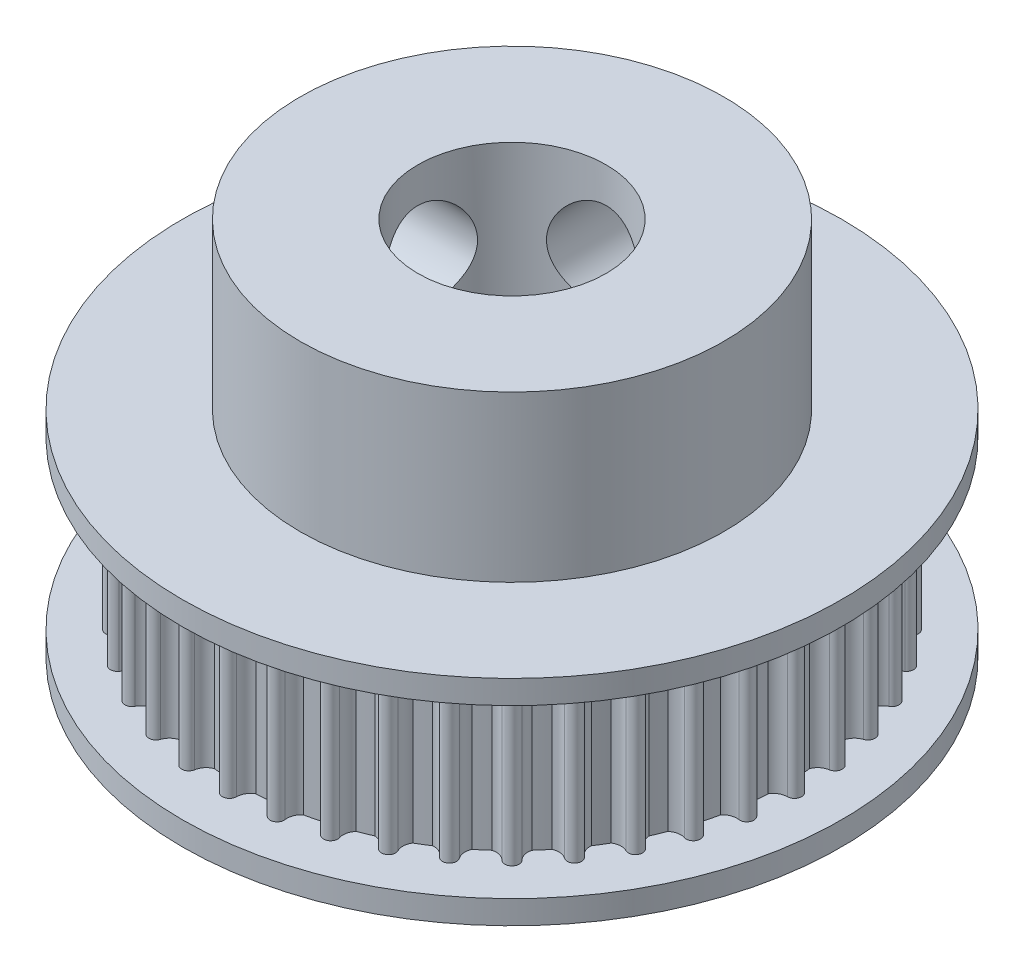
SolidWorks part; units mm, degrees
ref_plane "Front Plane" through (0, 0, 0) normal (0, 0, 1) x (1, 0, 0)
ref_plane "Top Plane" through (0, 0, 0) normal (0, 1, 0) x (1, 0, 0)
ref_plane "Right Plane" through (0, 0, 0) normal (1, 0, 0) x (0, 0, -1)
sketch "Sketch2" plane through (0, 0, 0) normal (0, 1, 0) x (1, 0, 0)
  circle A0 centre (0, 0) radius 14
  circle A1 centre (0, 0) radius 4
  dimension "D1" = 28
  dimension "D2" = 8
extrude "Boss-Extrude1" add sketch "Sketch2" along normal blind 15.5
sketch "Sketch3" plane through (0, 15.5, 0) normal (0, 1, 0) x (1, 0, 0)
  line L0 (0, 0) -> (0, 16.3628) construction
  circle A0 centre (0, 0) radius 14 construction
  circle A1 centre (0, 0) radius 14
  circle A2 centre (0, 0) radius 11.5 construction
  arc A3 (-0.3, 12.0013) -> (0.3, 12.0013) centre (0, 12) cw
  arc A4 (0.3, 12.0013) -> (0.6, 11.4843) centre (0.9, 12.004) ccw
  arc A5 (-0.3, 12.0013) -> (-0.6, 11.4843) centre (-0.9, 12.004) cw
  arc A6 (1.2039, 11.4368) -> (0.6, 11.4843) centre (0, 0) ccw
  arc A7 (1.5811, 11.9005) -> (2.1737, 11.8066) centre (1.8772, 11.8523) cw
  arc A8 (1.5811, 11.9005) -> (1.2039, 11.4368) centre (0.9889, 11.997) cw
  arc A9 (2.1737, 11.8066) -> (2.3892, 11.2491) centre (2.7667, 11.7154) ccw
  arc A10 (2.9782, 11.1077) -> (2.3892, 11.2491) centre (0, 0) ccw
  arc A11 (3.4233, 11.5066) -> (3.9939, 11.3212) centre (3.7082, 11.4127) cw
  arc A12 (3.4233, 11.5066) -> (2.9782, 11.1077) centre (2.8535, 11.6946) cw
  arc A13 (3.9939, 11.3212) -> (4.1195, 10.7368) centre (4.5654, 11.1383) ccw
  arc A14 (4.6792, 10.505) -> (4.1195, 10.7368) centre (0, 0) ccw
  arc A15 (5.1812, 10.8295) -> (5.7158, 10.5571) centre (5.4479, 10.6921) cw
  arc A16 (5.1812, 10.8295) -> (4.6792, 10.505) centre (4.6478, 11.1042) cw
  arc A17 (5.7158, 10.5571) -> (5.7484, 9.9602) centre (6.2516, 10.287) ccw
  arc A18 (6.2649, 9.6437) -> (5.7484, 9.9602) centre (0, 0) ccw
  arc A19 (6.8115, 9.8856) -> (7.2969, 9.5329) centre (7.0534, 9.7082) cw
  arc A20 (6.8115, 9.8856) -> (6.2649, 9.6437) centre (6.3276, 10.2404) cw
  arc A21 (7.2969, 9.5329) -> (7.2357, 8.9384) centre (7.7839, 9.1824) ccw
  arc A22 (7.6964, 8.5449) -> (7.2357, 8.9384) centre (0, 0) ccw
  arc A23 (8.2741, 8.6983) -> (8.6983, 8.2741) centre (8.4853, 8.4853) cw
  arc A24 (8.2741, 8.6983) -> (7.6964, 8.5449) centre (7.8517, 9.1245) cw
  arc A25 (8.6983, 8.2741) -> (8.5449, 7.6964) centre (9.1245, 7.8517) ccw
  arc A26 (8.9384, 7.2357) -> (8.5449, 7.6964) centre (0, 0) ccw
  arc A27 (9.5329, 7.2969) -> (9.8856, 6.8115) centre (9.7082, 7.0534) cw
  arc A28 (9.5329, 7.2969) -> (8.9384, 7.2357) centre (9.1824, 7.7839) cw
  arc A29 (9.8856, 6.8115) -> (9.6437, 6.2649) centre (10.2404, 6.3276) ccw
  arc A30 (9.9602, 5.7484) -> (9.6437, 6.2649) centre (0, 0) ccw
  arc A31 (10.5571, 5.7158) -> (10.8295, 5.1812) centre (10.6921, 5.4479) cw
  arc A32 (10.5571, 5.7158) -> (9.9602, 5.7484) centre (10.287, 6.2516) cw
  arc A33 (10.8295, 5.1812) -> (10.505, 4.6792) centre (11.1042, 4.6478) ccw
  arc A34 (10.7368, 4.1195) -> (10.505, 4.6792) centre (0, 0) ccw
  arc A35 (11.3212, 3.9939) -> (11.5066, 3.4233) centre (11.4127, 3.7082) cw
  arc A36 (11.3212, 3.9939) -> (10.7368, 4.1195) centre (11.1383, 4.5654) cw
  arc A37 (11.5066, 3.4233) -> (11.1077, 2.9782) centre (11.6946, 2.8535) ccw
  arc A38 (11.2491, 2.3892) -> (11.1077, 2.9782) centre (0, 0) ccw
  arc A39 (11.8066, 2.1737) -> (11.9005, 1.5811) centre (11.8523, 1.8772) cw
  arc A40 (11.8066, 2.1737) -> (11.2491, 2.3892) centre (11.7154, 2.7667) cw
  arc A41 (11.9005, 1.5811) -> (11.4368, 1.2039) centre (11.997, 0.9889) ccw
  arc A42 (11.4843, 0.6) -> (11.4368, 1.2039) centre (0, 0) ccw
  arc A43 (12.0013, 0.3) -> (12.0013, -0.3) centre (12, 0) cw
  arc A44 (12.0013, 0.3) -> (11.4843, 0.6) centre (12.004, 0.9) cw
  arc A45 (12.0013, -0.3) -> (11.4843, -0.6) centre (12.004, -0.9) ccw
  arc A46 (11.4368, -1.2039) -> (11.4843, -0.6) centre (0, 0) ccw
  arc A47 (11.9005, -1.5811) -> (11.8066, -2.1737) centre (11.8523, -1.8772) cw
  arc A48 (11.9005, -1.5811) -> (11.4368, -1.2039) centre (11.997, -0.9889) cw
  arc A49 (11.8066, -2.1737) -> (11.2491, -2.3892) centre (11.7154, -2.7667) ccw
  arc A50 (11.1077, -2.9782) -> (11.2491, -2.3892) centre (0, 0) ccw
  arc A51 (11.5066, -3.4233) -> (11.3212, -3.9939) centre (11.4127, -3.7082) cw
  arc A52 (11.5066, -3.4233) -> (11.1077, -2.9782) centre (11.6946, -2.8535) cw
  arc A53 (11.3212, -3.9939) -> (10.7368, -4.1195) centre (11.1383, -4.5654) ccw
  arc A54 (10.505, -4.6792) -> (10.7368, -4.1195) centre (0, 0) ccw
  arc A55 (10.8295, -5.1812) -> (10.5571, -5.7158) centre (10.6921, -5.4479) cw
  arc A56 (10.8295, -5.1812) -> (10.505, -4.6792) centre (11.1042, -4.6478) cw
  arc A57 (10.5571, -5.7158) -> (9.9602, -5.7484) centre (10.287, -6.2516) ccw
  arc A58 (9.6437, -6.2649) -> (9.9602, -5.7484) centre (0, 0) ccw
  arc A59 (9.8856, -6.8115) -> (9.5329, -7.2969) centre (9.7082, -7.0534) cw
  arc A60 (9.8856, -6.8115) -> (9.6437, -6.2649) centre (10.2404, -6.3276) cw
  arc A61 (9.5329, -7.2969) -> (8.9384, -7.2357) centre (9.1824, -7.7839) ccw
  arc A62 (8.5449, -7.6964) -> (8.9384, -7.2357) centre (0, 0) ccw
  arc A63 (8.6983, -8.2741) -> (8.2741, -8.6983) centre (8.4853, -8.4853) cw
  arc A64 (8.6983, -8.2741) -> (8.5449, -7.6964) centre (9.1245, -7.8517) cw
  arc A65 (8.2741, -8.6983) -> (7.6964, -8.5449) centre (7.8517, -9.1245) ccw
  arc A66 (7.2357, -8.9384) -> (7.6964, -8.5449) centre (0, 0) ccw
  arc A67 (7.2969, -9.5329) -> (6.8115, -9.8856) centre (7.0534, -9.7082) cw
  arc A68 (7.2969, -9.5329) -> (7.2357, -8.9384) centre (7.7839, -9.1824) cw
  arc A69 (6.8115, -9.8856) -> (6.2649, -9.6437) centre (6.3276, -10.2404) ccw
  arc A70 (5.7484, -9.9602) -> (6.2649, -9.6437) centre (0, 0) ccw
  arc A71 (5.7158, -10.5571) -> (5.1812, -10.8295) centre (5.4479, -10.6921) cw
  arc A72 (5.7158, -10.5571) -> (5.7484, -9.9602) centre (6.2516, -10.287) cw
  arc A73 (5.1812, -10.8295) -> (4.6792, -10.505) centre (4.6478, -11.1042) ccw
  arc A74 (4.1195, -10.7368) -> (4.6792, -10.505) centre (0, 0) ccw
  arc A75 (3.9939, -11.3212) -> (3.4233, -11.5066) centre (3.7082, -11.4127) cw
  arc A76 (3.9939, -11.3212) -> (4.1195, -10.7368) centre (4.5654, -11.1383) cw
  arc A77 (3.4233, -11.5066) -> (2.9782, -11.1077) centre (2.8535, -11.6946) ccw
  arc A78 (2.3892, -11.2491) -> (2.9782, -11.1077) centre (0, 0) ccw
  arc A79 (2.1737, -11.8066) -> (1.5811, -11.9005) centre (1.8772, -11.8523) cw
  arc A80 (2.1737, -11.8066) -> (2.3892, -11.2491) centre (2.7667, -11.7154) cw
  arc A81 (1.5811, -11.9005) -> (1.2039, -11.4368) centre (0.9889, -11.997) ccw
  arc A82 (0.6, -11.4843) -> (1.2039, -11.4368) centre (0, 0) ccw
  arc A83 (0.3, -12.0013) -> (-0.3, -12.0013) centre (0, -12) cw
  arc A84 (0.3, -12.0013) -> (0.6, -11.4843) centre (0.9, -12.004) cw
  arc A85 (-0.3, -12.0013) -> (-0.6, -11.4843) centre (-0.9, -12.004) ccw
  arc A86 (-1.2039, -11.4368) -> (-0.6, -11.4843) centre (0, 0) ccw
  arc A87 (-1.5811, -11.9005) -> (-2.1737, -11.8066) centre (-1.8772, -11.8523) cw
  arc A88 (-1.5811, -11.9005) -> (-1.2039, -11.4368) centre (-0.9889, -11.997) cw
  arc A89 (-2.1737, -11.8066) -> (-2.3892, -11.2491) centre (-2.7667, -11.7154) ccw
  arc A90 (-2.9782, -11.1077) -> (-2.3892, -11.2491) centre (0, 0) ccw
  arc A91 (-3.4233, -11.5066) -> (-3.9939, -11.3212) centre (-3.7082, -11.4127) cw
  arc A92 (-3.4233, -11.5066) -> (-2.9782, -11.1077) centre (-2.8535, -11.6946) cw
  arc A93 (-3.9939, -11.3212) -> (-4.1195, -10.7368) centre (-4.5654, -11.1383) ccw
  arc A94 (-4.6792, -10.505) -> (-4.1195, -10.7368) centre (0, 0) ccw
  arc A95 (-5.1812, -10.8295) -> (-5.7158, -10.5571) centre (-5.4479, -10.6921) cw
  arc A96 (-5.1812, -10.8295) -> (-4.6792, -10.505) centre (-4.6478, -11.1042) cw
  arc A97 (-5.7158, -10.5571) -> (-5.7484, -9.9602) centre (-6.2516, -10.287) ccw
  arc A98 (-6.2649, -9.6437) -> (-5.7484, -9.9602) centre (0, 0) ccw
  arc A99 (-6.8115, -9.8856) -> (-7.2969, -9.5329) centre (-7.0534, -9.7082) cw
  arc A100 (-6.8115, -9.8856) -> (-6.2649, -9.6437) centre (-6.3276, -10.2404) cw
  arc A101 (-7.2969, -9.5329) -> (-7.2357, -8.9384) centre (-7.7839, -9.1824) ccw
  arc A102 (-7.6964, -8.5449) -> (-7.2357, -8.9384) centre (0, 0) ccw
  arc A103 (-8.2741, -8.6983) -> (-8.6983, -8.2741) centre (-8.4853, -8.4853) cw
  arc A104 (-8.2741, -8.6983) -> (-7.6964, -8.5449) centre (-7.8517, -9.1245) cw
  arc A105 (-8.6983, -8.2741) -> (-8.5449, -7.6964) centre (-9.1245, -7.8517) ccw
  arc A106 (-8.9384, -7.2357) -> (-8.5449, -7.6964) centre (0, 0) ccw
  arc A107 (-9.5329, -7.2969) -> (-9.8856, -6.8115) centre (-9.7082, -7.0534) cw
  arc A108 (-9.5329, -7.2969) -> (-8.9384, -7.2357) centre (-9.1824, -7.7839) cw
  arc A109 (-9.8856, -6.8115) -> (-9.6437, -6.2649) centre (-10.2404, -6.3276) ccw
  arc A110 (-9.9602, -5.7484) -> (-9.6437, -6.2649) centre (0, 0) ccw
  arc A111 (-10.5571, -5.7158) -> (-10.8295, -5.1812) centre (-10.6921, -5.4479) cw
  arc A112 (-10.5571, -5.7158) -> (-9.9602, -5.7484) centre (-10.287, -6.2516) cw
  arc A113 (-10.8295, -5.1812) -> (-10.505, -4.6792) centre (-11.1042, -4.6478) ccw
  arc A114 (-10.7368, -4.1195) -> (-10.505, -4.6792) centre (0, 0) ccw
  arc A115 (-11.3212, -3.9939) -> (-11.5066, -3.4233) centre (-11.4127, -3.7082) cw
  arc A116 (-11.3212, -3.9939) -> (-10.7368, -4.1195) centre (-11.1383, -4.5654) cw
  arc A117 (-11.5066, -3.4233) -> (-11.1077, -2.9782) centre (-11.6946, -2.8535) ccw
  arc A118 (-11.2491, -2.3892) -> (-11.1077, -2.9782) centre (0, 0) ccw
  arc A119 (-11.8066, -2.1737) -> (-11.9005, -1.5811) centre (-11.8523, -1.8772) cw
  arc A120 (-11.8066, -2.1737) -> (-11.2491, -2.3892) centre (-11.7154, -2.7667) cw
  arc A121 (-11.9005, -1.5811) -> (-11.4368, -1.2039) centre (-11.997, -0.9889) ccw
  arc A122 (-11.4843, -0.6) -> (-11.4368, -1.2039) centre (0, 0) ccw
  arc A123 (-12.0013, -0.3) -> (-12.0013, 0.3) centre (-12, 0) cw
  arc A124 (-12.0013, -0.3) -> (-11.4843, -0.6) centre (-12.004, -0.9) cw
  arc A125 (-12.0013, 0.3) -> (-11.4843, 0.6) centre (-12.004, 0.9) ccw
  arc A126 (-11.4368, 1.2039) -> (-11.4843, 0.6) centre (0, 0) ccw
  arc A127 (-11.9005, 1.5811) -> (-11.8066, 2.1737) centre (-11.8523, 1.8772) cw
  arc A128 (-11.9005, 1.5811) -> (-11.4368, 1.2039) centre (-11.997, 0.9889) cw
  arc A129 (-11.8066, 2.1737) -> (-11.2491, 2.3892) centre (-11.7154, 2.7667) ccw
  arc A130 (-11.1077, 2.9782) -> (-11.2491, 2.3892) centre (0, 0) ccw
  arc A131 (-11.5066, 3.4233) -> (-11.3212, 3.9939) centre (-11.4127, 3.7082) cw
  arc A132 (-11.5066, 3.4233) -> (-11.1077, 2.9782) centre (-11.6946, 2.8535) cw
  arc A133 (-11.3212, 3.9939) -> (-10.7368, 4.1195) centre (-11.1383, 4.5654) ccw
  arc A134 (-10.505, 4.6792) -> (-10.7368, 4.1195) centre (0, 0) ccw
  arc A135 (-10.8295, 5.1812) -> (-10.5571, 5.7158) centre (-10.6921, 5.4479) cw
  arc A136 (-10.8295, 5.1812) -> (-10.505, 4.6792) centre (-11.1042, 4.6478) cw
  arc A137 (-10.5571, 5.7158) -> (-9.9602, 5.7484) centre (-10.287, 6.2516) ccw
  arc A138 (-9.6437, 6.2649) -> (-9.9602, 5.7484) centre (0, 0) ccw
  arc A139 (-9.8856, 6.8115) -> (-9.5329, 7.2969) centre (-9.7082, 7.0534) cw
  arc A140 (-9.8856, 6.8115) -> (-9.6437, 6.2649) centre (-10.2404, 6.3276) cw
  arc A141 (-9.5329, 7.2969) -> (-8.9384, 7.2357) centre (-9.1824, 7.7839) ccw
  arc A142 (-8.5449, 7.6964) -> (-8.9384, 7.2357) centre (0, 0) ccw
  arc A143 (-8.6983, 8.2741) -> (-8.2741, 8.6983) centre (-8.4853, 8.4853) cw
  arc A144 (-8.6983, 8.2741) -> (-8.5449, 7.6964) centre (-9.1245, 7.8517) cw
  arc A145 (-8.2741, 8.6983) -> (-7.6964, 8.5449) centre (-7.8517, 9.1245) ccw
  arc A146 (-7.2357, 8.9384) -> (-7.6964, 8.5449) centre (0, 0) ccw
  arc A147 (-7.2969, 9.5329) -> (-6.8115, 9.8856) centre (-7.0534, 9.7082) cw
  arc A148 (-7.2969, 9.5329) -> (-7.2357, 8.9384) centre (-7.7839, 9.1824) cw
  arc A149 (-6.8115, 9.8856) -> (-6.2649, 9.6437) centre (-6.3276, 10.2404) ccw
  arc A150 (-5.7484, 9.9602) -> (-6.2649, 9.6437) centre (0, 0) ccw
  arc A151 (-5.7158, 10.5571) -> (-5.1812, 10.8295) centre (-5.4479, 10.6921) cw
  arc A152 (-5.7158, 10.5571) -> (-5.7484, 9.9602) centre (-6.2516, 10.287) cw
  arc A153 (-5.1812, 10.8295) -> (-4.6792, 10.505) centre (-4.6478, 11.1042) ccw
  arc A154 (-4.1195, 10.7368) -> (-4.6792, 10.505) centre (0, 0) ccw
  arc A155 (-3.9939, 11.3212) -> (-3.4233, 11.5066) centre (-3.7082, 11.4127) cw
  arc A156 (-3.9939, 11.3212) -> (-4.1195, 10.7368) centre (-4.5654, 11.1383) cw
  arc A157 (-3.4233, 11.5066) -> (-2.9782, 11.1077) centre (-2.8535, 11.6946) ccw
  arc A158 (-2.3892, 11.2491) -> (-2.9782, 11.1077) centre (0, 0) ccw
  arc A159 (-2.1737, 11.8066) -> (-1.5811, 11.9005) centre (-1.8772, 11.8523) cw
  arc A160 (-2.1737, 11.8066) -> (-2.3892, 11.2491) centre (-2.7667, 11.7154) cw
  arc A161 (-1.5811, 11.9005) -> (-1.2039, 11.4368) centre (-0.9889, 11.997) ccw
  arc A162 (-0.6, 11.4843) -> (-1.2039, 11.4368) centre (0, 0) ccw
  point P31 (1.2289, 11.447)
  point P328 (0, 0)
  dimension "D1" = 23
  dimension "D4" = 0.6
  dimension "D2" = 0.3
  dimension "D3" = 0.3
  dimension "D5" = 12
extrude "Cut-Extrude1" cut sketch "Sketch3" against normal blind 7.1 from offset 1 offset against normal yes
sketch "Sketch4" plane through (0, 0, 0) normal (0, 0, 1) x (1, 0, 0)
  circle A0 centre (0, 3.75) radius 2
  dimension "D1" = 4
  dimension "D2" = 3.75
extrude "Cut-Extrude2" cut sketch "Sketch4" against normal up to next
sketch "Sketch5" plane through (0, 0, 0) normal (1, 0, 0) x (0, 0, -1)
  circle A0 centre (0, 3.75) radius 2
  dimension "D1" = 4
  dimension "D2" = 3.75
extrude "Cut-Extrude3" cut sketch "Sketch5" against normal up to next
sketch "Sketch6" plane through (0, 15.5, 0) normal (0, 1, 0) x (1, 0, 0)
  circle A0 centre (0, 0) radius 9
  circle A1 centre (0, 0) radius 4 construction
  circle A2 centre (0, 0) radius 4
  dimension "D1" = 18
extrude "Boss-Extrude2" add sketch "Sketch6" along normal blind 7
sketch "Sketch7" plane through (0, 0, 0) normal (0, 0, 1) x (1, 0, 0)
  line L0 (9, 22.5) -> (-9, 22.5) construction
  circle A0 centre (0, 19) radius 2
  dimension "D1" = 4
  dimension "D2" = 3.5
extrude "Cut-Extrude4" cut sketch "Sketch7" against normal up to next
sketch "Sketch8" plane through (0, 0, 0) normal (1, 0, 0) x (0, 0, -1)
  line L0 (9, 22.5) -> (-9, 22.5) construction
  circle A0 centre (0, 19) radius 2
  dimension "D1" = 4
  dimension "D2" = 3.5
extrude "Cut-Extrude5" cut sketch "Sketch8" against normal up to next
sketch "Sketch9" plane through (0, 0, 0) normal (0, -1, 0) x (1, 0, 0)
  circle A0 centre (0, 0) radius 14 construction
  circle A1 centre (0, 0) radius 14
extrude "Cut-Extrude6" cut sketch "Sketch9" against normal blind 6.4
